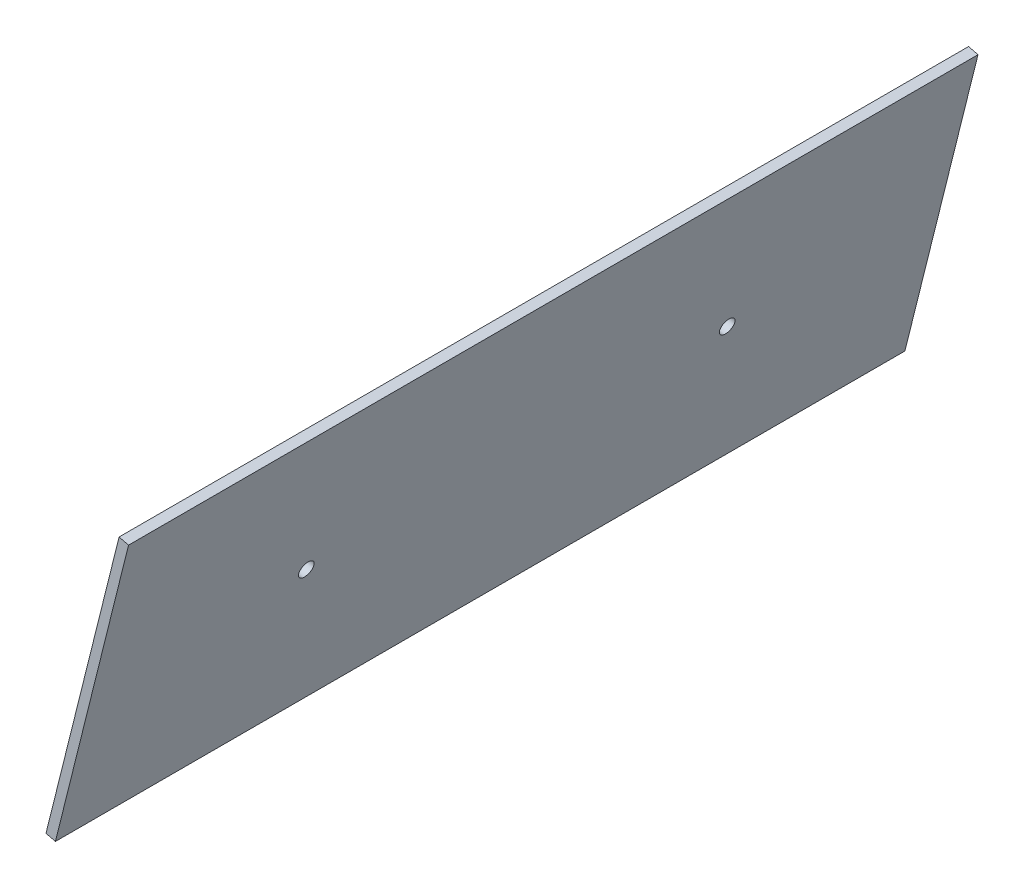
SolidWorks part; units mm, degrees
material "5052-H34"
ref_plane "Front Plane" through (0, 0, 0) normal (0, 0, 1) x (1, 0, 0)
ref_plane "Top Plane" through (0, 0, 0) normal (0, 1, 0) x (1, 0, 0)
ref_plane "Right Plane" through (0, 0, 0) normal (1, 0, 0) x (0, 0, -1)
sketch "Sketch1" plane through (0, 0, 0) normal (0, 0, 1) x (1, 0, 0)
  line L1 (-37.6295, -38.8249) -> (-13.7518, 56.9433)
  line L2 (-40.7102, -38.0568) -> (-16.8325, 57.7114)
  line L4 (-16.8325, 57.7114) -> (-13.7518, 56.9433)
  line L5 (-37.6295, -38.8249) -> (-40.7102, -38.0568)
  point P2 (0, 0)
  dimension "D2" = 98.7
  dimension "D3" = 3.175
extrude "Boss-Extrude1" add sketch "Sketch1" along normal blind 277.475 contours L1 L4 L2 L5
sketch "Sketch2" plane through (-26.3136, 6.5607, 0) normal (0.9703, -0.2419, 0) x (0, 0, -1)
  line L2 (-277.475, -46.775) -> (-277.475, 51.925) construction
  line L3 (0, -46.775) -> (0, 51.925) construction
  circle A0 centre (-207.475, 2.6168) radius 2.5
  circle A1 centre (-70, 2.6168) radius 2.5
  point P2 (0, 0)
  dimension "D1" = 5
  dimension "D2" = 5
  dimension "D3" = 70
  dimension "D4" = 70
extrude "Cut-Extrude1" cut sketch "Sketch2" against normal up to next
